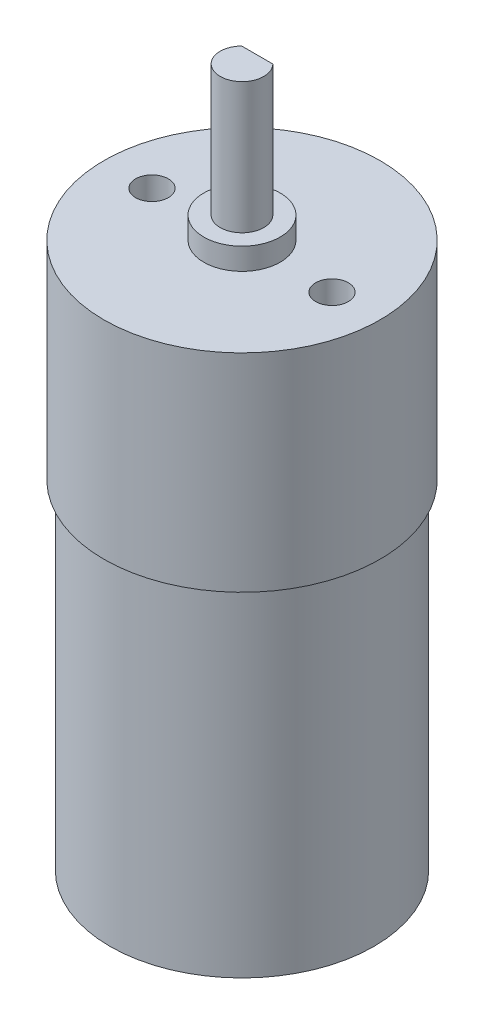
SolidWorks part; units mm, degrees
ref_plane "Спереди" through (0, 0, 0) normal (0, 0, 1) x (1, 0, 0)
ref_plane "Сверху" through (0, 0, 0) normal (0, 1, 0) x (1, 0, 0)
ref_plane "Справа" through (0, 0, 0) normal (1, 0, 0) x (0, 0, -1)
sketch "Sketch1" plane through (0, 0, 0) normal (0, 1, 0) x (1, 0, 0)
  circle A0 centre (0, 0) radius 12.1
  dimension "D1" = 24.2
extrude "Boss-Extrude1" add sketch "Sketch1" along normal blind 31
sketch "Sketch2" plane through (0, 31, 0) normal (0, 1, 0) x (1, 0, 0)
  circle A0 centre (0, 0) radius 12.65
  dimension "D1" = 25.3
extrude "Boss-Extrude2" add sketch "Sketch2" along normal blind 19
sketch "Sketch3" plane through (0, 50, 0) normal (0, 1, 0) x (1, 0, 0)
  circle A0 centre (0, 0) radius 3.5
  dimension "D1" = 7
extrude "Boss-Extrude3" add sketch "Sketch3" along normal blind 2
sketch "Sketch4" plane through (0, 52, 0) normal (0, 1, 0) x (1, 0, 0)
  circle A0 centre (0, 0) radius 2
  dimension "D1" = 4
extrude "Boss-Extrude4" add sketch "Sketch4" along normal blind 12
sketch "Sketch5" plane through (0, 50, 0) normal (0, 1, 0) x (1, 0, 0)
  line L0 (0, 0) -> (8.25, 0) construction
  line L1 (0, 0) -> (-8.25, 0) construction
  circle A0 centre (8.25, 0) radius 1.5
  circle A1 centre (-8.25, 0) radius 1.5
  dimension "D2" = 3
  dimension "D1" = 16.5
extrude "Cut-Extrude1" cut sketch "Sketch5" against normal blind 6
sketch "Sketch6" plane through (0, 64, 0) normal (0, 1, 0) x (1, 0, 0)
  line L0 (-1.4283, 1.4) -> (1.4283, 1.4)
  line L1 (0, 0) -> (0, 1.4) construction
  line L2 (0, 0) -> (0, -2) construction
  circle A0 centre (0, 0) radius 2 construction
  arc A1 (-1.4283, 1.4) -> (1.4283, 1.4) centre (0, 0) cw
  circle A2 centre (0, 0) radius 2 construction
  dimension "D1" = 3.4
extrude "Cut-Extrude2" cut sketch "Sketch6" against normal blind 10
